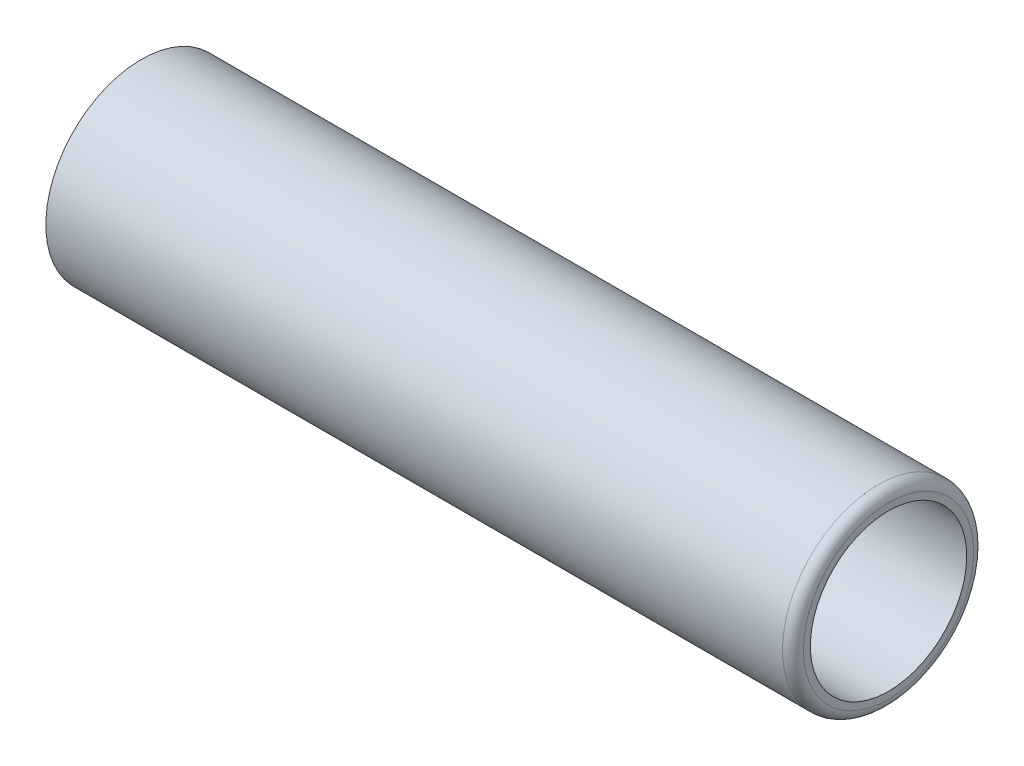
SolidWorks part; units mm, degrees
ref_plane "Front Plane" through (0, 0, 0) normal (0, 0, 1) x (1, 0, 0)
ref_plane "Top Plane" through (0, 0, 0) normal (0, 1, 0) x (1, 0, 0)
ref_plane "Right Plane" through (0, 0, 0) normal (1, 0, 0) x (0, 0, -1)
sketch "Sketch1" plane through (0, 0, 0) normal (1, 0, 0) x (0, 0, -1)
  circle A0 centre (0, 0) radius 6.985
  circle A1 centre (0, 0) radius 5.715
  dimension "D1" = 13.97
  dimension "D2" = 1.27
extrude "Boss-Extrude1" add sketch "Sketch1" along normal blind 54.61
fillet "Fillet1" radius 0.762 1 edges at (54.61, 0, -6.985)
